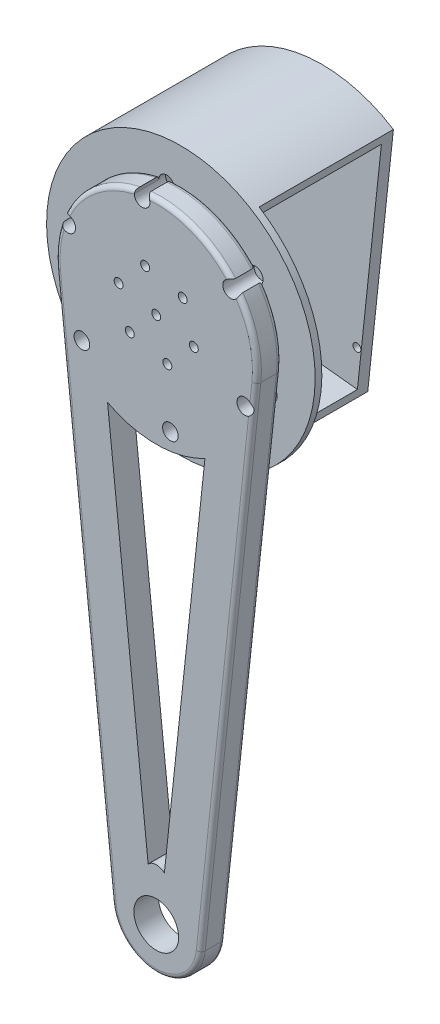
SolidWorks part; units mm, degrees
ref_plane "前视基准面" through (0, 0, 0) normal (0, 0, 1) x (1, 0, 0)
ref_plane "上视基准面" through (0, 0, 0) normal (0, 1, 0) x (1, 0, 0)
ref_plane "右视基准面" through (0, 0, 0) normal (1, 0, 0) x (0, 0, -1)
sketch "草图1" plane through (0, 0, 0) normal (0, 0, 1) x (1, 0, 0)
  line L1 (-44.7446, -4.7872) -> (-19.8865, -237.1277)
  line L2 (44.7446, -4.7872) -> (19.8865, -237.1277)
  arc A2 (-44.7446, -4.7872) -> (44.7446, -4.7872) centre (0, 0) cw
  arc A3 (-19.8865, -237.1277) -> (19.8865, -237.1277) centre (0, -235) ccw
extrude "凸台-拉伸1" add sketch "草图1" along normal blind 11
sketch "草图2" plane through (0, 0, 0) normal (0, 0, -1) x (-1, 0, 0)
  line L0 (0, 0) -> (0, -95.701) construction
  circle A0 centre (0, -235.836) radius 10
extrude "切除-拉伸1" cut sketch "草图2" against normal blind 11
fillet "圆角1" radius 2 8 edges at (0, 45, 11) (0, -255, 11) (32.3156, -120.9574, 11) (-32.3156, -120.9574, 11) (0, -255, 0) (-32.3156, -120.9574, 0) (0, 45, 0) (32.3156, -120.9574, 0)
sketch "草图3" plane through (0, 0, 11) normal (0, 0, 1) x (1, 0, 0)
  circle A0 centre (0, -235.836) radius 10
sketch "草图4" plane through (0, 0, 0) normal (0, 0, -1) x (-1, 0, 0)
  line L0 (0, 0) -> (0, -235.836) construction
  line L1 (-21.7598, -44.6823) -> (-3.626, -214.173)
  line L3 (21.7598, -44.6823) -> (3.6153, -214.2726)
  line L4 (17.8979, -236.9149) -> (42.756, -4.5745) construction
  line L5 (-42.756, -4.5745) -> (-17.8979, -236.9149) construction
  arc A2 (21.7598, -44.6823) -> (-21.7598, -44.6823) centre (0, -3.3509) cw
  arc A3 (-3.626, -214.173) -> (3.6153, -214.2726) centre (-0.0551, -217.8435) cw
  point P7 (0, -44.6823)
extrude "切除-拉伸2" cut sketch "草图4" against normal blind 20
sketch "草图6" plane through (0, 0, 11) normal (0, 0, 1) x (1, 0, 0)
  circle A0 centre (-16.7892, 3.9603) radius 2
  circle A1 centre (-4.9649, 16.52) radius 2
  circle A2 centre (11.8243, 12.5598) radius 2
  circle A3 centre (16.7892, -3.9603) radius 2
  circle A4 centre (4.9649, -16.52) radius 2
  circle A5 centre (-11.8243, -12.5598) radius 2
  point P15 (0, 0)
  dimension "D1" = 6
  dimension "D2" = 17.25
extrude "切除-拉伸4" cut sketch "草图6" against normal blind 33
sketch "草图7" plane through (0, 0, 0) normal (0, 0, -1) x (-1, 0, 0)
  circle A0 centre (0, 0) radius 60
extrude "凸台-拉伸2" add sketch "草图7" along normal blind 3
sketch "草图8" plane through (0, 0, -3) normal (0, 0, -1) x (-1, 0, 0)
  circle A0 centre (-33.2304, 26.4951) radius 3.5
  circle A1 centre (6.3302, 42.0259) radius 3.5
  circle A2 centre (39.5606, 15.5308) radius 3.5
  circle A3 centre (33.2304, -26.4951) radius 3.5
  circle A4 centre (-6.3302, -42.0259) radius 3.5
  circle A5 centre (-39.5606, -15.5308) radius 3.5
  point P16 (0, 0)
  dimension "D1" = 42.5
  dimension "D2" = 6
extrude "切除-拉伸5" cut sketch "草图8" against normal blind 32
sketch "草图9" plane through (0, 0, -3) normal (0, 0, -1) x (-1, 0, 0)
  circle A0 centre (0, 0) radius 60 construction
  arc A1 (-20.5076, -56.3865) -> (-31.9725, 50.7717) centre (0, 0) ccw
  spline S0 degree 1 poles (-20.5076, -56.3865) (-31.9725, 50.7717) knots 0 0 1 1
  dimension "D1" = 107.7697
extrude "凸台-拉伸3" add sketch "草图9" along normal blind 60 contours S0 A1
sketch "草图10" plane through (0, 0, -63) normal (0, 0, -1) x (-1, 0, 0)
  line L1 (-5.1842, 50.1141) -> (-31.6096, 47.3804)
  line L2 (-31.9725, 50.7717) -> (-20.5076, -56.3865) construction
  line L3 (5.1842, -50.1141) -> (-20.8803, -52.9027)
  line L4 (-31.6096, 47.3804) -> (-20.8803, -52.9027)
  arc A0 (5.1842, -50.1141) -> (-5.1842, 50.1141) centre (0, 0) ccw
extrude "切除-拉伸6" cut sketch "草图10" against normal blind 55 from offset 5 offset against normal yes
sketch "草图11" plane through (0, 0, -63) normal (0, 0, -1) x (-1, 0, 0)
  circle A0 centre (21.0287, 37.3558) radius 1.75
  circle A1 centre (41.1102, 11.7665) radius 1.75
  circle A2 centre (37.2156, -20.5276) radius 1.75
  circle A3 centre (11.6264, -40.6091) radius 1.75
  circle A4 centre (-20.6677, -36.7145) radius 1.75
  circle A5 centre (-40.7492, -11.1252) radius 1.75
  circle A6 centre (-36.8546, 21.1689) radius 1.75
  circle A7 centre (-11.2654, 41.2504) radius 1.75
  point P19 (0.1805, 0.3207)
  dimension "D1" = 8
extrude "切除-拉伸7" cut sketch "草图11" against normal blind 55
sketch "草图12" plane through (0, 0, 0) normal (0, 1, 0) x (1, 0, 0)
  line L0 (26.9095, 3) -> (-9.8307, 3)
  line L1 (5.1842, 3) -> (31.6096, 3) construction
  line L2 (-9.8307, 3) -> (-9.8307, 20.1924)
  line L3 (-9.8307, 20.1924) -> (26.9095, 20.1924)
  line L4 (26.9095, 20.1924) -> (26.9095, 3)
extrude "切除-拉伸11" cut sketch "草图12" against normal blind 86
sketch "草图13" plane through (0, 0, -3) normal (0, 0, -1) x (-1, 0, 0)
  circle A0 centre (0, 0) radius 2
extrude "切除-拉伸12" cut sketch "草图13" against normal blind 16
